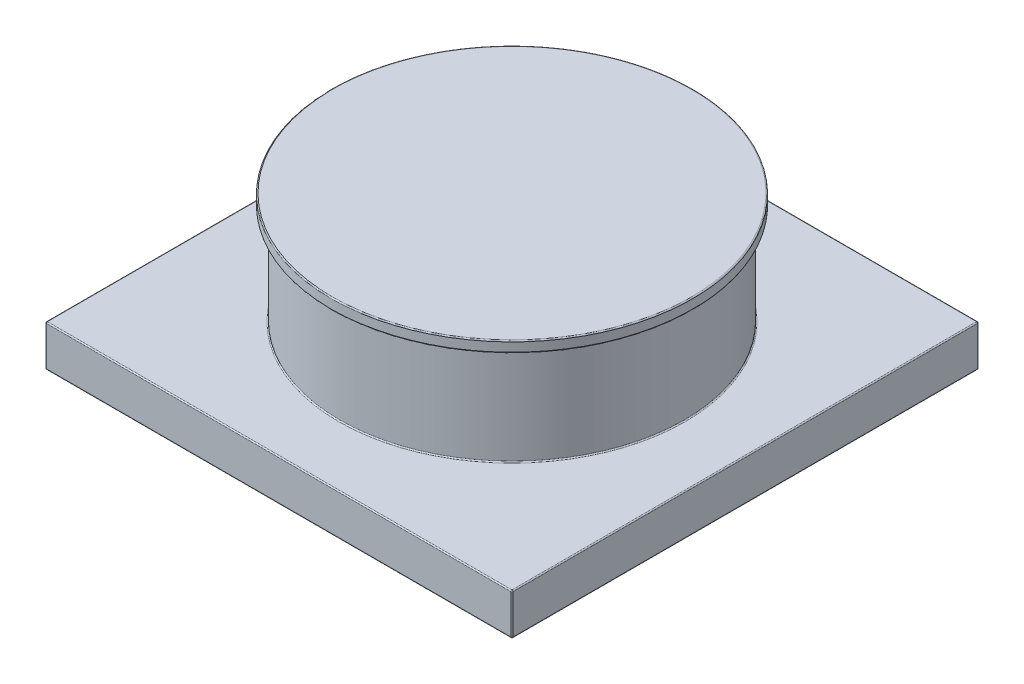
SolidWorks part; units mm, degrees
ref_plane "Front Plane" through (0, 0, 0) normal (0, 0, 1) x (1, 0, 0)
ref_plane "Top Plane" through (0, 0, 0) normal (0, 1, 0) x (1, 0, 0)
ref_plane "Right Plane" through (0, 0, 0) normal (1, 0, 0) x (0, 0, -1)
sketch "Sketch1" plane through (0, 0, 0) normal (0, 1, 0) x (1, 0, 0)
  line L1 (0, 0) -> (2100, 0)
  line L2 (0, 0) -> (0, 2100)
  line L3 (0, 2100) -> (2100, 2100)
  line L4 (2100, 0) -> (2100, 2100)
  dimension "D1" = 2100
  dimension "D2" = 2100
extrude "Boss-Extrude1" add sketch "Sketch1" along normal blind 186
sketch "Sketch2" plane through (0, 186, 0) normal (0, 1, 0) x (1, 0, 0)
  circle A0 centre (1050, 1050) radius 775
  dimension "D1" = 1550
extrude "Boss-Extrude2" add sketch "Sketch2" along normal blind 501
sketch "Sketch3" plane through (0, 687, 0) normal (0, 1, 0) x (1, 0, 0)
  circle A0 centre (1050, 1050) radius 813.3417
extrude "Boss-Extrude3" add sketch "Sketch3" against normal blind 50
sketch "Sketch4" plane through (0, 0, 0) normal (0, -1, 0) x (1, 0, 0)
  circle A0 centre (546.652, -600) radius 12.5
  circle A2 centre (1556.652, -600) radius 12.5
  circle A3 centre (546.652, -1500) radius 12.5
  circle A4 centre (1556.652, -1500) radius 12.5
  dimension "D3" = 25
  dimension "D1" = 1010
  dimension "D2" = 900
  dimension "D4" = 1010
  dimension "D5" = 900
extrude "Cut-Extrude1" cut sketch "Sketch4" against normal blind 10
fillet "Fillet1" radius 5 15 edges at (0, 0, -1050) (0, 93, 0) (0, 93, -2100) (1050, 0, -2100) (2100, 93, -2100) (2100, 0, -1050) (1050, 0, 0) (2100, 93, 0) (2100, 186, -1050) (1050, 186, -2100) (1050, 186, 0) (0, 186, -1050) (1050, 186, -1825) (1050, 637, -236.6583) (1050, 687, -236.6583)
